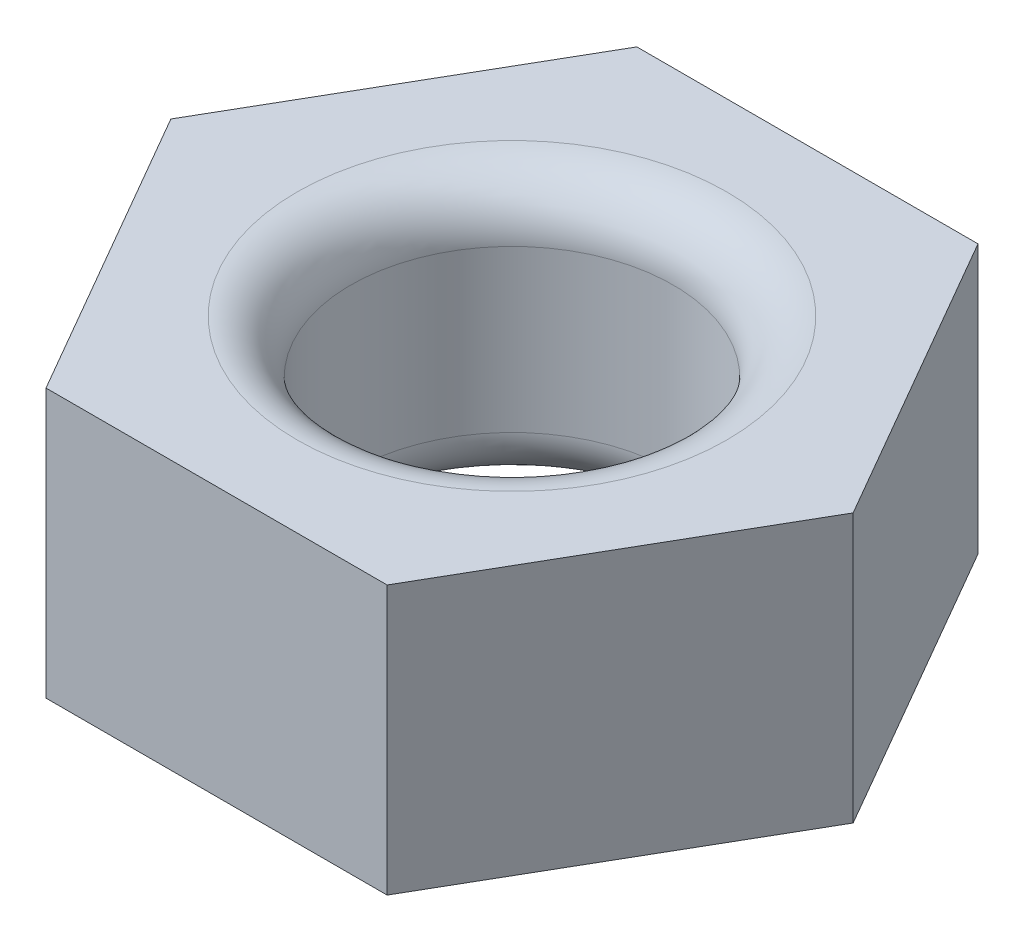
SolidWorks part; units mm, degrees
ref_plane "Front Plane" through (0, 0, 0) normal (0, 0, 1) x (1, 0, 0)
ref_plane "Top Plane" through (0, 0, 0) normal (0, 1, 0) x (1, 0, 0)
ref_plane "Right Plane" through (0, 0, 0) normal (1, 0, 0) x (0, 0, -1)
sketch "Sketch1" plane through (0, 0, 0) normal (0, 1, 0) x (1, 0, 0)
  line L1 (-3.1754, 0) -> (-1.5877, -2.75)
  line L2 (-1.5877, -2.75) -> (1.5877, -2.75)
  line L3 (1.5877, -2.75) -> (3.1754, 0)
  line L4 (3.1754, 0) -> (1.5877, 2.75)
  line L5 (1.5877, 2.75) -> (-1.5877, 2.75)
  line L6 (-1.5877, 2.75) -> (-3.1754, 0)
  circle A0 centre (0, 0) radius 2.75 construction
  circle A1 centre (0, 0) radius 1.5
extrude "Boss-Extrude1" add sketch "Sketch1" along normal blind 2.5
fillet "Fillet1" radius 0.5 2 edges at (0, 0, 1.5) (0, 2.5, 1.5)
